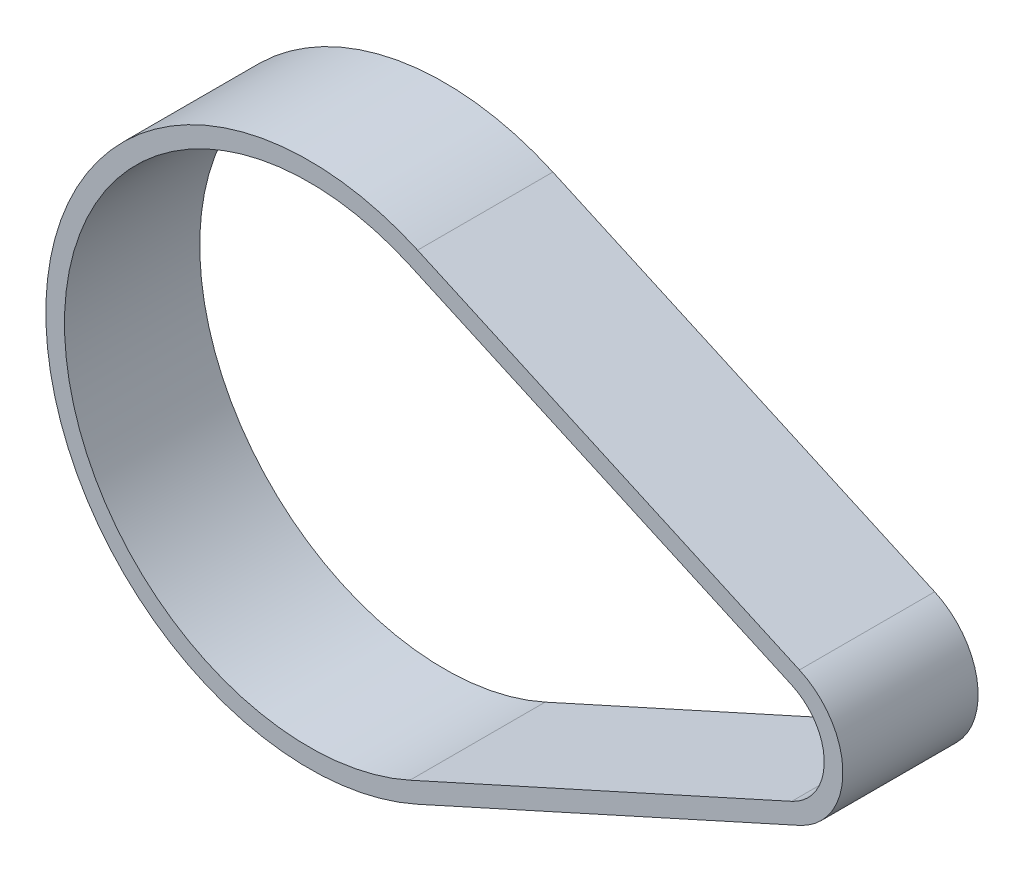
SolidWorks part; units mm, degrees
ref_plane "Front" through (0, 0, 0) normal (0, 0, 1) x (1, 0, 0)
ref_plane "Top" through (0, 0, 0) normal (0, 1, 0) x (1, 0, 0)
ref_plane "Right" through (0, 0, 0) normal (1, 0, 0) x (0, 0, -1)
sketch "Эскиз1" plane through (0, 0, 0) normal (0, 0, 1) x (1, 0, 0)
  line L0 (0, 0) -> (34, 0) construction
  line L1 (8.0199, 17.7405) -> (36.2506, 4.9784)
  line L2 (36.2506, -4.9784) -> (8.0199, -17.7405)
  line L3 (35.6821, -3.7209) -> (7.4514, -16.4831)
  line L4 (7.4514, 16.4831) -> (35.6821, 3.7209)
  arc A0 (8.0199, 17.7405) -> (8.0199, -17.7405) centre (0, 0) ccw
  arc A1 (36.2506, -4.9784) -> (36.2506, 4.9784) centre (34, 0) ccw
  arc A2 (7.4514, 16.4831) -> (7.4514, -16.4831) centre (0, 0) ccw
  arc A3 (35.6821, -3.7209) -> (35.6821, 3.7209) centre (34, 0) ccw
  dimension "D1" = 38.9382
  dimension "D3" = 10.9269
  dimension "D2" = 34
  dimension "D4" = 1.38
extrude "Бобышка-Вытянуть1" add sketch "Эскиз1" against normal blind 10
